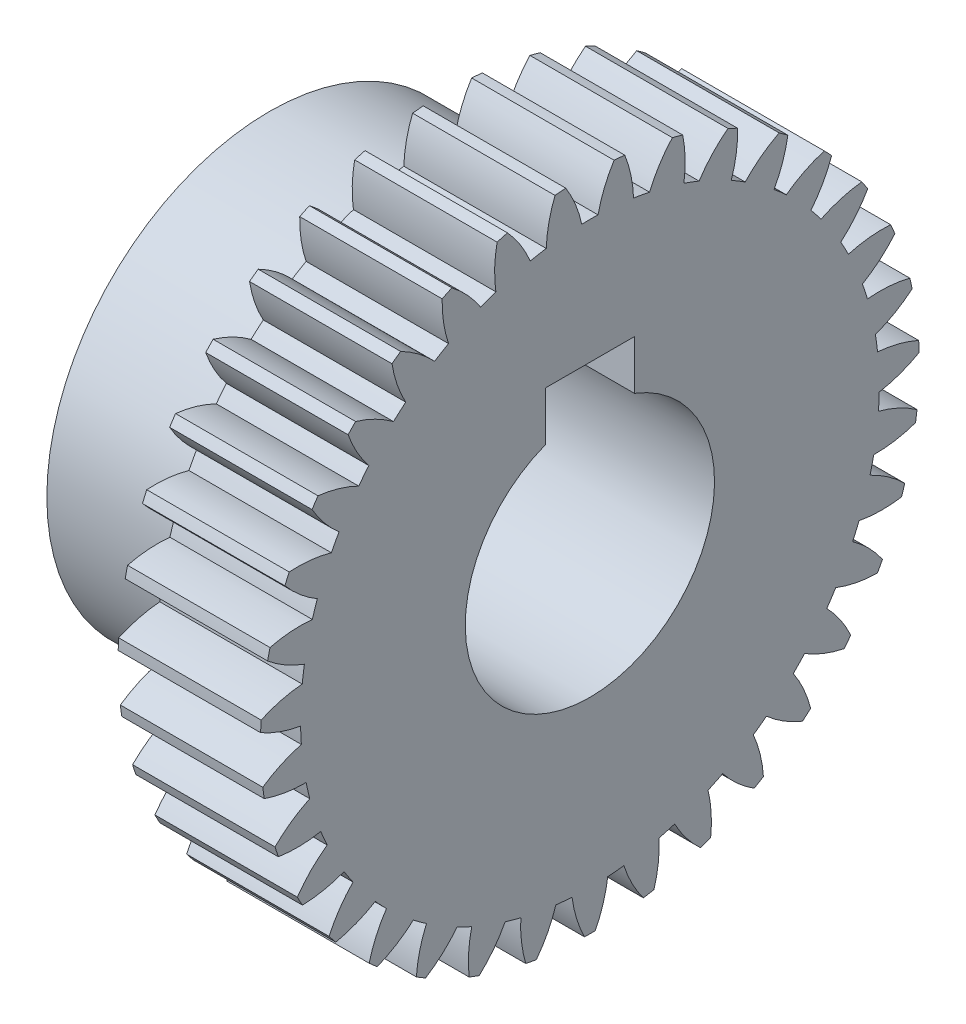
SolidWorks part; units mm, degrees
ref_plane "Plane1" through (0, 0, 0) normal (0, 0, 1) x (1, 0, 0)
ref_plane "Plane2" through (0, 0, 0) normal (0, 1, 0) x (1, 0, 0)
ref_plane "Plane3" through (0, 0, 0) normal (1, 0, 0) x (0, 0, -1)
other "Configuration Table"
sketch "HoldingSke" plane through (0, 0, 0) normal (0, 1, 0) x (1, 0, 0)
  line L0 (0, 0) -> (0.8192, -0.5736)
  line L1 (-15, 0) -> (100, 0) construction
  line L2 (0, 0) -> (-2.1039, 2.3779)
  line L3 (0, 0) -> (-11.863, 4.5341)
  line L4 (0, 0) -> (7.0742, 4.9534)
  line L5 (0, 0) -> (-16.8652, -6.2902)
  line L6 (0, 0) -> (-6.6317, -4.4744)
  line L7 (-2.1039, 2.3779) -> (1.7706, 19.956)
  line L8 (-76.2, 54.61) -> (-73.9, 54.61)
  line L9 (-71.009, 38.7566) -> (-53.1078, 45.2721)
  line L10 (-76.2, 71.12) -> (104.1128, 71.12)
  line L11 (0, 0) -> (-8, 0)
  line L12 (-76.2, 101.6) -> (-76.162, 101.6)
  line L13 (24.9733, 27.94) -> (52.9518, 28.4284)
  line L14 (24.9733, 27.94) -> (24.9743, 27.94)
  line L15 (24.9733, 27.94) -> (100.4006, 29.5858)
  line L16 (-63.627, -1) -> (-12.827, -1)
  circle A0 centre (0, 0) radius 7
  circle A1 centre (0, 0) radius 12.5
  circle A2 centre (0, 0) radius 12.5
  circle A3 centre (0, 0) radius 7
  dimension "MHD" = 25
  dimension "Hub_dia" = 25
  dimension "Num_teeth" = 35
  dimension "Pitch" = 1
  dimension "Overall_len" = 18
  dimension "Show_teeth" = 35
  dimension "Thickness" = 8
  dimension "OAL" = 18.0001
  dimension "T_dim" = 2.3
  dimension "Ap" = 20
  dimension "H" = 19.05
  dimension "Pitch_radius" = 180.3128
  dimension "Width" = 8
  dimension "Backlash" = 0.038
  dimension "Addendum_fac" = 1
  dimension "Dedendum_fac" = 1.25
  dimension "Clearance_fac" = 0.25
  dimension "Dedendum_add" = 0.001
  dimension "Module" = 1
sketch "BasProSke" plane through (0, 0, 0) normal (0, 1, 0) x (1, 0, 0)
  line L0 (-10, 0) -> (60, 0) construction
  line L1 (0, 0) -> (0, 18.5)
  line L2 (0, 0) -> (8, 0)
  line L3 (8, 0) -> (8, 18.5)
  line L4 (8, 18.5) -> (0, 18.5)
  dimension "Thickness" = 8
  dimension "Diameter" = 37
revolve "Base-Revolve" add sketch "BasProSke" angle 360 about L0
sketch "TooCutSke" plane through (0, 0, 0) normal (1, 0, 0) x (0, 0, -1)
  line L1 (0, 0) -> (0, 107) construction
  line L2 (0, 0) -> (-0.8516, 17.4793) construction
  line L3 (0, 0) -> (-3.1347, 34.8297) construction
  line L4 (-0.8516, 17.4793) -> (-1.5674, 17.4148) construction
  arc A0 (0.4564, 16.2426) -> (-0.4564, 16.2426) centre (0, 0) ccw
  arc A1 (1.373, 18.4745) -> (-1.373, 18.4745) centre (0, 0) ccw
  circle A2 centre (0, 0) radius 17.5 construction
  circle A3 centre (0, 0) radius 16.4446 construction
  arc A4 (-0.4564, 16.2426) -> (-1.373, 18.4745) centre (-7.293, 14.739) ccw
  arc A5 (1.373, 18.4745) -> (0.4564, 16.2426) centre (7.293, 14.739) ccw
  dimension "Root_dia" = 32.498
  dimension "Overcut_dia" = 37.0508
  dimension "Pitch_dia" = 35
  dimension "Base_dia" = 32.8892
  dimension "Flank_rad" = 7
  dimension "Half_ang" = 5.143
  dimension "Half_CT" = 0.7186
extrude "ToothCut" cut sketch "TooCutSke" along normal through all
fillet "Breaks" [suppressed] radius 0.02
fillet "RootFillets" [suppressed] radius 0.251
pattern_circular "TeethCuts" count 35 every 10.286 about axis through (-10, 0, 0) along (1, 0, 0) of "ToothCut", "RootFillets", "Breaks"
sketch "HubNeaOneSke" plane through (0, 0, 0) normal (-1, 0, 0) x (0, 0, 1)
  circle A0 centre (0, 0) radius 12.5
  dimension "Diameter" = 25
extrude "HubNearOne" add sketch "HubNeaOneSke" along normal blind 10.0001
sketch "HubNeaBotSke" plane through (0, 0, 0) normal (-1, 0, 0) x (0, 0, 1)
  circle A0 centre (0, 0) radius 12.5
  dimension "Diameter" = 25
extrude "HubNearBoth" [suppressed] add sketch "HubNeaBotSke" along normal blind 5
ref_plane "FarPln" through (8, 0, 0) normal (1, 0, 0) x (0, 0, -1)
sketch "HubFarSke" plane through (8, 0, 0) normal (1, 0, 0) x (0, 0, -1)
  circle A0 centre (0, 0) radius 12.5
  dimension "Diameter" = 25
extrude "HubFar" [suppressed] add sketch "HubFarSke" along normal blind 5
sketch "BorSke" plane through (0, 0, 0) normal (1, 0, 0) x (0, 0, -1)
  circle A0 centre (0, 0) radius 7
extrude "Bore" cut sketch "BorSke" along normal mid plane 36.0001
sketch "KeySke" plane through (0, 0, 0) normal (1, 0, 0) x (0, 0, -1)
  line L0 (-2.5, 0) -> (-2.5, 9.3)
  line L1 (-2.5, 9.3) -> (2.5, 9.3)
  line L2 (2.5, 9.3) -> (2.5, 0)
  line L3 (0, 0) -> (0, 34) construction
  line L4 (-2.5, 0) -> (2.5, 0)
  dimension "Width" = 5
extrude "Keyway" cut sketch "KeySke" along normal mid plane 36.0001
pattern_circular "Keyway2" [suppressed] count 2 every 90 about axis through (-10, 0, 0) along (1, 0, 0)
equation "' \"Module@HoldingSke\" = 6.35"
equation "' \"Num_teeth@HoldingSke\" = 12"
equation "' \"Ap@HoldingSke\" =  20"
equation "' \"Ap@HoldingSke\" = 20"
equation "' \"Width@HoldingSke\" = 0.5 * 25.4"
equation "' \"Hub_dia@HoldingSke\"= 1 * 25.4"
equation "' \"Hub_dia@HoldingSke\" = 1 * 25.4"
equation "' \"Overall_len@HoldingSke\" = 1.0 * 25.4"
equation "' \"Bore@HoldingSke\" = 0.75 * 25.4"
equation "' \"T_dim@HoldingSke\" = 0.1 * 25.4"
equation "' \"Width@KeySke\" = 0.25 * 25.4"
equation "' \"Show_teeth@HoldingSke\" = 13"
equation "' \"Backlash@HoldingSke\" = 0.009 * 25.4"
equation "' \"Addendum_fac@HoldingSke\" = 1.0"
equation "' \"Dedendum_fac@HoldingSke\" = 1.25"
equation "' \"Dedendum_add@HoldingSke\" = 0.00005 * 25.4"
equation "' \"Clearance_fac@HoldingSke\" = 0.25"
equation "\"Pitch@HoldingSke\" = 1 / \"Module@HoldingSke\""
equation "\"Overcut_dia@TooCutSke\" = (\"Num_teeth@HoldingSke\" + 2 * \"Addendum_fac@HoldingSke\") / \"Pitch@HoldingSke\" + 0.002 * 25.4"
equation "\"Pitch_dia@TooCutSke\" = \"Num_teeth@HoldingSke\" / \"Pitch@HoldingSke\""
equation "\"Base_dia@TooCutSke\" = \"Num_teeth@HoldingSke\" / \"Pitch@HoldingSke\" * cos((\"Ap@HoldingSke\"  * 3.14159265 / 180))"
equation "\"Root_dia@TooCutSke\" = (\"Num_teeth@HoldingSke\" + 2) / \"Pitch@HoldingSke\" - 2 * (\"Addendum_fac@HoldingSke\" + \"Dedendum_fac@HoldingSke\") / \"Pitch@HoldingSke\" - \"Dedendum_add@HoldingSke\" * 2"
equation "\"Half_ang@TooCutSke\" = 180 / \"Num_teeth@HoldingSke\""
equation "\"Half_CT@TooCutSke\" = \"Num_teeth@HoldingSke\" / \"Pitch@HoldingSke\" * sin((3.14159265 / 2 / \"Num_teeth@HoldingSke\")) / 2 - 7 * \"Backlash@HoldingSke\" / 4"
equation "\"Flank_rad@TooCutSke\" = \"Num_teeth@HoldingSke\" / \"Pitch@HoldingSke\" / 5"
equation "\"Radius@RootFillets\" = \"Clearance_fac@HoldingSke\" / \"Pitch@HoldingSke\" + \"Dedendum_add@HoldingSke\""
equation "\"Break_rad@Breaks\" = 0.02 / \"Pitch@HoldingSke\""
equation "\"Thickness@HoldingSke\" = \"Width@HoldingSke\""
equation "\"OAL@HoldingSke\" = \"Thickness@HoldingSke\""
equation "\"MHD@HoldingSke\" = (\"Num_teeth@HoldingSke\" + 2) / \"Pitch@HoldingSke\" - 2 * (\"Addendum_fac@HoldingSke\" + \"Dedendum_fac@HoldingSke\")  / \"Pitch@HoldingSke\" - \"Dedendum_add@HoldingSke\" * 2"
equation "\"MBD@HoldingSke\" = (\"Num_teeth@HoldingSke\" + 2) / \"Pitch@HoldingSke\" - 2 * (\"Addendum_fac@HoldingSke\" + \"Dedendum_fac@HoldingSke\")  / \"Pitch@HoldingSke\" - \"Dedendum_add@HoldingSke\" * 2 - 0.002 * 25.4"
equation "\"MHD@HoldingSke\" = ((sgn( \"MHD@HoldingSke\" - \"Hub_dia@HoldingSke\" )-1)*( \"MHD@HoldingSke\" - \"Hub_dia@HoldingSke\" ))/-2+ \"Hub_dia@HoldingSke\""
equation "\"MBD@HoldingSke\" = ((sgn( \"MBD@HoldingSke\" - \"Bore@HoldingSke\" )-1)*( \"MBD@HoldingSke\" - \"Bore@HoldingSke\" ))/-2+ \"Bore@HoldingSke\""
equation "\"OAL@HoldingSke\" = ((sgn( \"OAL@HoldingSke\" - \"Overall_len@HoldingSke\" )+1)*( \"OAL@HoldingSke\" - \"Overall_len@HoldingSke\" ))/2 + \"Overall_len@HoldingSke\" + 0.000002 * 25.4"
equation "\"Num_teeth@TeethCuts\" = int( \"Show_teeth@HoldingSke\" ) + 1"
equation "\"Num_teeth@TeethCuts\" = ((sgn( \"Num_teeth@TeethCuts\" - \"Num_teeth@HoldingSke\" )-1)*( \"Num_teeth@TeethCuts\" - \"Num_teeth@HoldingSke\" ))/-2+ \"Num_teeth@HoldingSke\""
equation "\"Num_teeth@TeethCuts\" = ((sgn( \"Num_teeth@TeethCuts\" - 2.0)+1)*( \"Num_teeth@TeethCuts\" - 2.0))/2 +2.0"
equation "\"Angle@TeethCuts\" = 360.0 / \"Num_teeth@HoldingSke\""
equation "\"Diameter@BasProSke\" = (\"Num_teeth@HoldingSke\" + 2 * \"Addendum_fac@HoldingSke\") / \"Pitch@HoldingSke\""
equation "\"Thickness@BasProSke\"  = \"Thickness@HoldingSke\""
equation "' \"Fillet_rad@BasProSke\" =  \"Thickness@HoldingSke\" * 0.05"
equation "' \"Fillet_rad@BasProSke\" = \"Thickness@HoldingSke\" * 0.05"
equation "\"MHD@HoldingSke\" = ((sgn( \"MHD@HoldingSke\" - \"Root_dia@TooCutSke\" )-1)*( \"MHD@HoldingSke\" - \"Root_dia@TooCutSke\" ))/-2+ \"Root_dia@TooCutSke\""
equation "\"Diameter@HubNeaOneSke\" = \"MHD@HoldingSke\""
equation "\"Length@HubNearOne\" = \"OAL@HoldingSke\" - \"Thickness@BasProSke\""
equation "\"Diameter@HubNeaBotSke\" = \"MHD@HoldingSke\""
equation "\"Length@HubNearBoth\" = ( \"OAL@HoldingSke\" - \"Thickness@BasProSke\" ) / 2.0"
equation "\"Thickness@FarPln\" = \"Thickness@BasProSke\""
equation "\"Diameter@HubFarSke\" = \"MHD@HoldingSke\""
equation "\"Length@HubFar\" = ( \"OAL@HoldingSke\" - \"Thickness@BasProSke\" ) / 2.0"
equation "\"Diameter@BorSke\" = \"MBD@HoldingSke\""
equation "\"D1@Bore\" = \"OAL@HoldingSke\" * 2.0"
equation "\"D1@Keyway\" = \"OAL@HoldingSke\" * 2.0"
equation "\"Offset@KeySke\" = \"T_dim@HoldingSke\" + \"MBD@HoldingSke\" / 2.0"
